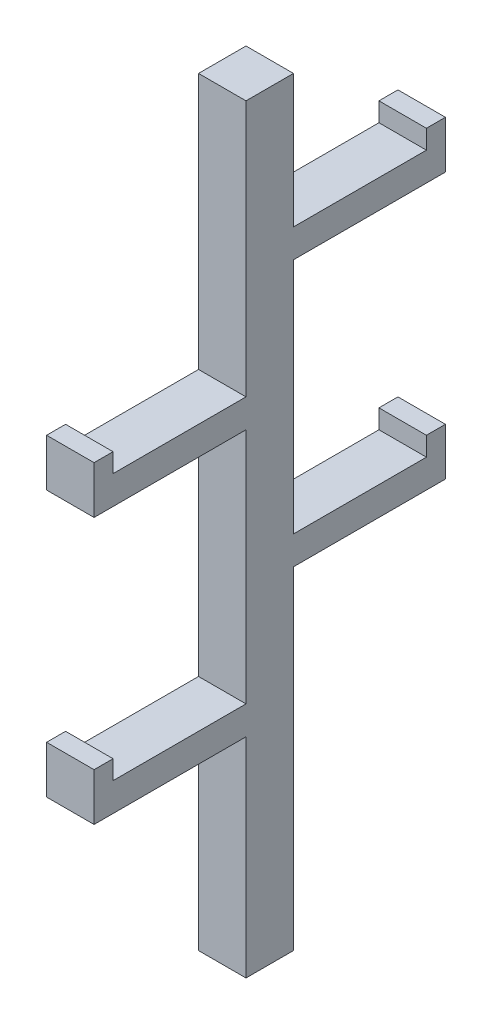
SolidWorks part; units mm, degrees
ref_plane "Front Plane" through (0, 0, 0) normal (0, 0, 1) x (1, 0, 0)
ref_plane "Top Plane" through (0, 0, 0) normal (0, 1, 0) x (1, 0, 0)
ref_plane "Right Plane" through (0, 0, 0) normal (1, 0, 0) x (0, 0, -1)
sketch "Sketch1" plane through (0, 0, 0) normal (0, 1, 0) x (1, 0, 0)
  line L1 (3.175, -3.175) -> (-3.175, -3.175)
  line L2 (3.175, -3.175) -> (3.175, 3.175)
  line L3 (3.175, 3.175) -> (-3.175, 3.175)
  line L4 (-3.175, -3.175) -> (-3.175, 3.175)
  line L5 (3.175, -3.175) -> (-3.175, 3.175) construction
  line L6 (3.175, 3.175) -> (-3.175, -3.175) construction
  point P0 (0, 0)
  dimension "D1" = 6.35
  dimension "D2" = 6.35
extrude "Boss-Extrude1" add sketch "Sketch1" along normal blind 101.6
sketch "Sketch4" plane through (0, 0, 3.175) normal (0, 0, 1) x (1, 0, 0)
  line L0 (-3.175, 101.6) -> (-3.175, 0) construction
  line L1 (-3.175, 27.94) -> (3.175, 27.94)
  line L2 (-3.175, 27.94) -> (-3.175, 31.75)
  line L3 (-3.175, 31.75) -> (3.175, 31.75)
  line L4 (3.175, 27.94) -> (3.175, 31.75)
  line L5 (3.175, 101.6) -> (3.175, 0) construction
  line L6 (-3.175, 0) -> (3.175, 0) construction
  line L8 (-3.175, 63.5) -> (3.175, 63.5)
  line L9 (-3.175, 63.5) -> (-3.175, 67.31)
  line L10 (-3.175, 67.31) -> (3.175, 67.31)
  line L11 (3.175, 63.5) -> (3.175, 67.31)
  dimension "D1" = 27.94
  dimension "D2" = 3.81
  dimension "D3" = 3.81
  dimension "D4" = 31.75
extrude "Boss-Extrude2" add sketch "Sketch4" along normal blind 20.32
sketch "Sketch5" plane through (0, 31.75, 0) normal (0, 1, 0) x (1, 0, 0)
  line L0 (3.175, -23.495) -> (3.175, -3.175) construction
  line L1 (-3.175, -23.495) -> (3.175, -23.495)
  line L2 (-3.175, -23.495) -> (-3.175, -20.955)
  line L3 (-3.175, -20.955) -> (3.175, -20.955)
  line L4 (3.175, -23.495) -> (3.175, -20.955)
  dimension "D1" = 2.54
extrude "Boss-Extrude3" add sketch "Sketch5" along normal blind 2.54
sketch "Sketch6" plane through (0, 0, -3.175) normal (0, 0, -1) x (-1, 0, 0)
  line L0 (-3.175, 101.6) -> (-3.175, 0) construction
  line L1 (-3.175, 44.45) -> (3.175, 44.45)
  line L2 (-3.175, 44.45) -> (-3.175, 48.26)
  line L3 (-3.175, 48.26) -> (3.175, 48.26)
  line L4 (3.175, 44.45) -> (3.175, 48.26)
  line L5 (3.175, 101.6) -> (3.175, 0) construction
  line L7 (-3.175, 80.01) -> (3.175, 80.01)
  line L8 (-3.175, 80.01) -> (-3.175, 83.82)
  line L9 (-3.175, 83.82) -> (3.175, 83.82)
  line L10 (3.175, 80.01) -> (3.175, 83.82)
  line M6 (3.175, 0) -> (3.175, 101.6)
  line M8 (-3.175, 101.6) -> (-3.175, 0)
  dimension "D1" = 44.45
  dimension "D2" = 3.81
  dimension "D3" = 31.75
  dimension "D4" = 3.81
extrude "Boss-Extrude4" add sketch "Sketch6" along normal blind 20.32 contours L9 L7 M8 M6 | L3 L4 L1 L2
sketch "Sketch7" plane through (0, 48.26, 0) normal (0, 1, 0) x (1, 0, 0)
  line L0 (-3.175, 23.495) -> (-3.175, 3.175) construction
  line L1 (3.175, 23.495) -> (-3.175, 23.495)
  line L2 (3.175, 23.495) -> (3.175, 20.955)
  line L3 (3.175, 20.955) -> (-3.175, 20.955)
  line L4 (-3.175, 23.495) -> (-3.175, 20.955)
  dimension "D1" = 2.54
extrude "Boss-Extrude5" add sketch "Sketch7" along normal blind 2.54
sketch "Sketch8" plane through (0, 67.31, 0) normal (0, 1, 0) x (1, 0, 0)
  line L0 (-3.175, -23.495) -> (-3.175, -3.175) construction
  line L1 (3.175, -23.495) -> (-3.175, -23.495)
  line L2 (3.175, -23.495) -> (3.175, -20.955)
  line L3 (3.175, -20.955) -> (-3.175, -20.955)
  line L4 (-3.175, -23.495) -> (-3.175, -20.955)
  line L5 (-3.175, -3.175) -> (3.175, -3.175) construction
  dimension "D1" = 17.78
sketch "Sketch9" plane through (0, 83.82, 0) normal (0, 1, 0) x (1, 0, 0)
  line L0 (3.175, 23.495) -> (3.175, 3.175) construction
  line L1 (-3.175, 23.495) -> (3.175, 23.495)
  line L2 (-3.175, 23.495) -> (-3.175, 20.955)
  line L3 (-3.175, 20.955) -> (3.175, 20.955)
  line L4 (3.175, 23.495) -> (3.175, 20.955)
  line L5 (3.175, 3.175) -> (-3.175, 3.175) construction
  dimension "D1" = 17.78
extrude "Boss-Extrude6" add sketch "Sketch9" along normal blind 2.54
extrude "Boss-Extrude7" add sketch "Sketch8" along normal blind 2.54
